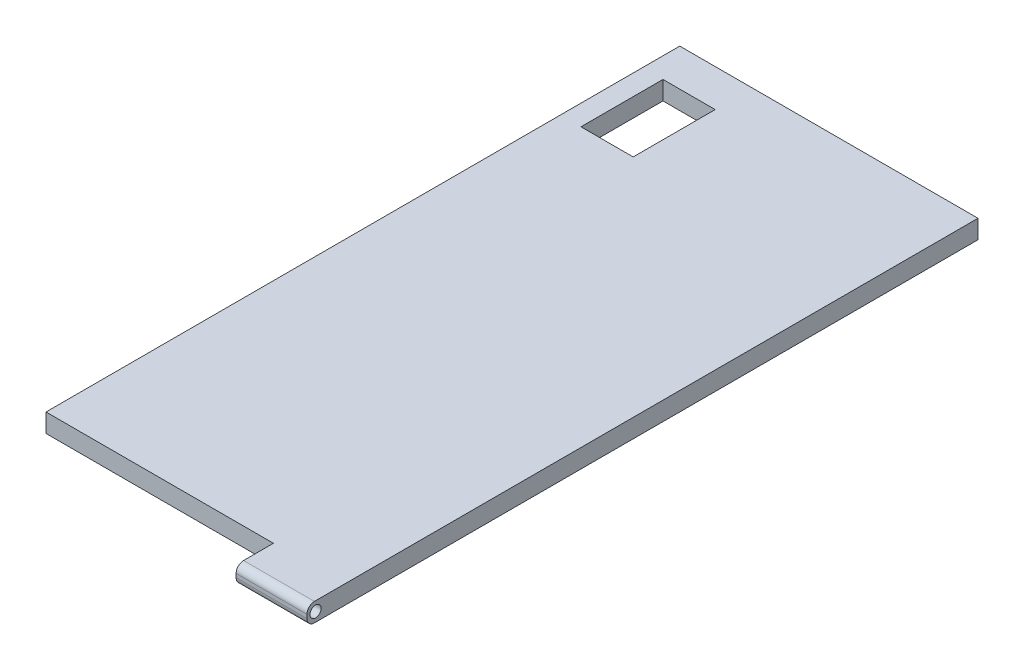
SolidWorks part; units mm, degrees
ref_plane "Front Plane" through (0, 0, 0) normal (0, 0, 1) x (1, 0, 0)
ref_plane "Top Plane" through (0, 0, 0) normal (0, 1, 0) x (1, 0, 0)
ref_plane "Right Plane" through (0, 0, 0) normal (1, 0, 0) x (0, 0, -1)
sketch "Sketch4" plane through (0, 0, 0) normal (0, 1, 0) x (1, 0, 0)
  line L1 (-20, -42.5) -> (20, -42.5)
  line L2 (-20, -42.5) -> (-20, 42.5)
  line L3 (-20, 42.5) -> (20, 42.5)
  line L4 (20, -42.5) -> (20, 42.5)
  line L5 (-20, -42.5) -> (20, 42.5) construction
  line L6 (-20, 42.5) -> (20, -42.5) construction
  point P0 (0, 0)
  dimension "D1" = 85
  dimension "D2" = 40
extrude "Boss-Extrude1" add sketch "Sketch4" along normal blind 2.5
sketch "Sketch5" plane through (0, 2.5, 0) normal (0, 1, 0) x (1, 0, 0)
  line L1 (20, -42.5) -> (10.5, -42.5)
  line L2 (20, -42.5) -> (20, -47.5)
  line L3 (20, -47.5) -> (10.5, -47.5)
  line L4 (10.5, -42.5) -> (10.5, -47.5)
  dimension "D1" = 5
  dimension "D2" = 9.5
extrude "Boss-Extrude2" add sketch "Sketch5" against normal blind 2.5
sketch "Sketch12" plane through (0, 2.5, 0) normal (0, 1, 0) x (1, 0, 0)
  line L0 (20, 42.5) -> (-20, 42.5) construction
  line L1 (-17.25, 37.5) -> (-10.25, 37.5)
  line L2 (-17.25, 37.5) -> (-17.25, 26.5)
  line L3 (-17.25, 26.5) -> (-10.25, 26.5)
  line L4 (-10.25, 37.5) -> (-10.25, 26.5)
  line L5 (-20, 42.5) -> (-20, -42.5) construction
  dimension "D1" = 11
  dimension "D2" = 7
  dimension "D3" = 5
  dimension "D4" = 2.75
extrude "Cut-Extrude1" cut sketch "Sketch12" against normal blind 5
fillet "Fillet4" radius 1 1 edges at (15.25, 2.5, 47.5)
fillet "Fillet5" radius 1 1 edges at (15.25, 0, 47.5)
sketch "Sketch13" plane through (10.5, 0, 0) normal (-1, 0, 0) x (0, 0, 1)
  line L0 (47.5, 1.25) -> (46.35, 1.25) construction
  line L1 (47.5, 1) -> (47.5, 1.5) construction
  circle A0 centre (46.35, 1.25) radius 0.75
  dimension "D1" = 1.5
  dimension "D2" = 1.15
extrude "Cut-Extrude2" cut sketch "Sketch13" against normal blind 10
